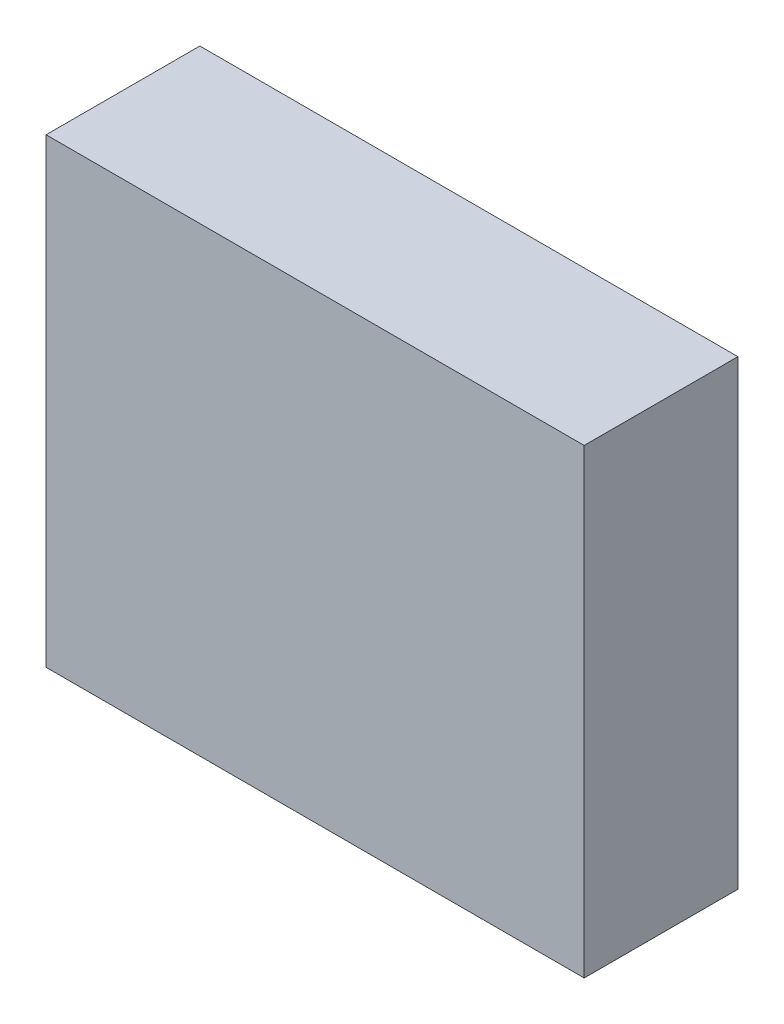
SolidWorks part; units mm, degrees
ref_plane "前视基准面" through (0, 0, 0) normal (0, 0, 1) x (1, 0, 0)
ref_plane "上视基准面" through (0, 0, 0) normal (0, 1, 0) x (1, 0, 0)
ref_plane "右视基准面" through (0, 0, 0) normal (1, 0, 0) x (0, 0, -1)
other "Configuration Table"
sketch "草图1" plane through (0, 0, 0) normal (0, 0, 1) x (1, 0, 0)
  line L1 (-35, -30) -> (35, -30)
  line L2 (-35, -30) -> (-35, 30)
  line L3 (-35, 30) -> (35, 30)
  line L4 (35, -30) -> (35, 30)
  line L5 (-35, -30) -> (35, 30) construction
  line L6 (-35, 30) -> (35, -30) construction
  point P0 (0, 0)
extrude "凸台-拉伸1" add sketch "草图1" along normal blind 20
